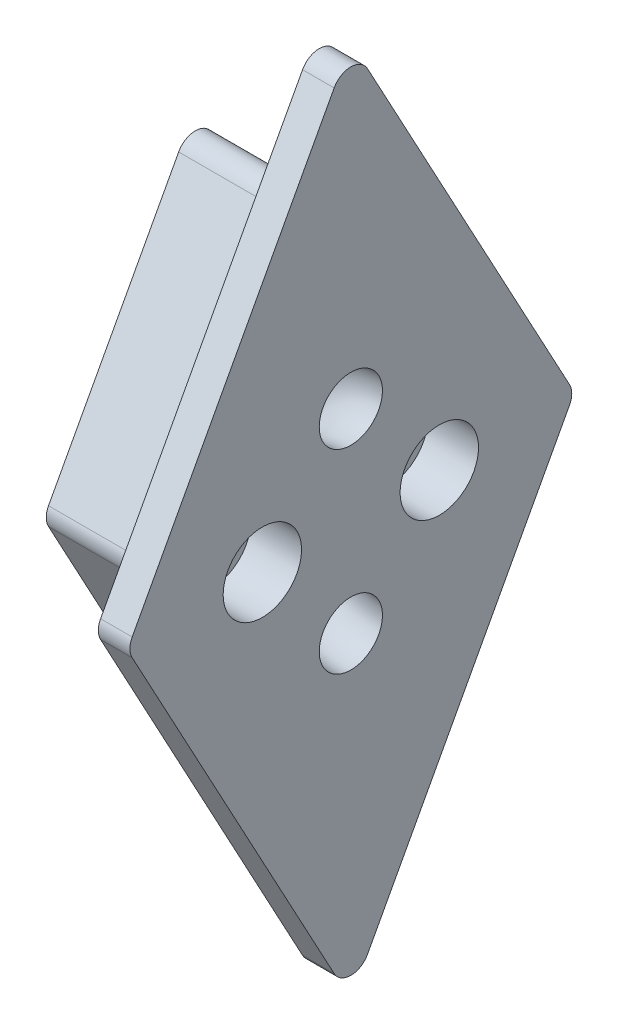
SolidWorks part; units mm, degrees
ref_plane "Front" through (0, 0, 0) normal (0, 0, 1) x (1, 0, 0)
ref_plane "Top" through (0, 0, 0) normal (0, 1, 0) x (1, 0, 0)
ref_plane "Right" through (0, 0, 0) normal (1, 0, 0) x (0, 0, -1)
sketch "Sketch1" plane through (0, 0, 0) normal (1, 0, 0) x (0, 0, -1)
  line L1 (0, -28.2575) -> (15.24, 0)
  line L2 (0, -28.2575) -> (-15.24, 0)
  line L3 (-15.24, 0) -> (0, 28.2575)
  line L4 (15.24, 0) -> (0, 28.2575)
  line L5 (0, -28.2575) -> (0, 28.2575) construction
  line L6 (-15.24, 0) -> (15.24, 0) construction
  point P0 (0, 0)
  dimension "D1" = 30.48
  dimension "D2" = 56.515
extrude "Boss-Extrude1" add sketch "Sketch1" along normal blind 12.446
sketch "Sketch6" plane through (12.446, 0, 0) normal (1, 0, 0) x (0, 0, -1)
  line L14 (-22.4547, 0) -> (0, -41.6347)
  line L15 (0, -41.6347) -> (22.4547, 0)
  line L16 (22.4547, 0) -> (0, 41.6347)
  line L17 (0, 41.6347) -> (-22.4547, 0)
  line L18 (-22.4547, 0) -> (0, -41.6347)
  line L19 (0, -41.6347) -> (22.4547, 0)
  line L20 (22.4547, 0) -> (0, 41.6347)
  line L21 (0, 41.6347) -> (-22.4547, 0)
  dimension "D1" = 6.35
extrude "Boss-Extrude3" add sketch "Sketch6" along normal blind 3.175
fillet "Fillet1" radius 1.905 8 edges at (14.0335, 41.6347, 0) (14.0335, 0, 22.4547) (14.0335, -41.6347, 0) (14.0335, 0, -22.4547) (6.223, -28.2575, 0) (6.223, 0, -15.24) (6.223, 0, 15.24) (6.223, 28.2575, 0)
sketch "Sketch7" plane through (0, 0, 0) normal (0, 1, 0) x (1, 0, 0)
  line L0 (0, 0) -> (25.2725, 0) construction
  line L1 (15.875, 0) -> (15.875, -10.3712) construction
  line L2 (15.621, 21.9669) -> (15.621, 1.6767) construction
  circle A0 centre (6.096, 0) radius 3.175
  dimension "D1" = 6.35
  dimension "D2" = 6.35
revolve "Cut-Revolve2" cut sketch "Sketch7" angle 360 about L1
sketch "Sketch8" plane through (15.621, 0, 0) normal (1, 0, 0) x (0, 0, -1)
  line L0 (0, 0) -> (8.89, 0) construction
  line L1 (0, 0) -> (0, 3.2594) construction
  circle A0 centre (8.89, 0) radius 3.937
  circle A1 centre (-8.89, 0) radius 3.937
  dimension "D2" = 7.874
  dimension "D1" = 8.89
extrude "Cut-Extrude3" cut sketch "Sketch8" against normal blind 5.08
sketch "Sketch9" plane through (10.541, 0, 0) normal (1, 0, 0) x (0, 0, -1)
  line L0 (0, 0) -> (0, 4.0921) construction
  circle A0 centre (8.89, 0) radius 2.5527
  circle A1 centre (-8.89, 0) radius 2.5527
  dimension "D1" = 5.1054
extrude "Cut-Extrude4" cut sketch "Sketch9" against normal through all
sketch "Sketch10" [suppressed] plane through (15.875, 0, 0) normal (1, 0, 0) x (0, 0, -1)
  line L0 (0, 0) -> (0, 8.2156) construction
  line L1 (13.6525, 2.7496) -> (8.89, 5.4993)
  line L2 (8.89, 5.4993) -> (4.1275, 2.7496)
  line L3 (4.1275, 2.7496) -> (4.1275, -2.7496)
  line L4 (4.1275, -2.7496) -> (8.89, -5.4993)
  line L5 (8.89, -5.4993) -> (13.6525, -2.7496)
  line L6 (13.6525, -2.7496) -> (13.6525, 2.7496)
  line L7 (-13.6525, -2.7496) -> (-13.6525, 2.7496)
  line L8 (-8.89, -5.4993) -> (-13.6525, -2.7496)
  line L9 (-4.1275, -2.7496) -> (-8.89, -5.4993)
  line L10 (-4.1275, 2.7496) -> (-4.1275, -2.7496)
  line L11 (-8.89, 5.4993) -> (-4.1275, 2.7496)
  line L12 (-13.6525, 2.7496) -> (-8.89, 5.4993)
  circle A0 centre (8.89, 0) radius 4.7625 construction
  circle A1 centre (-8.89, 0) radius 4.7625 construction
  point P1 (13.6525, 0)
  dimension "D1" = 9.525
sketch "Sketch11" [suppressed] plane through (15.621, 0, 0) normal (1, 0, 0) x (0, 0, -1)
  line L0 (0, 0) -> (8.89, 0) construction
  line L1 (0, 0) -> (0, 10.0261) construction
  circle A0 centre (8.89, 0) radius 3.175
  circle A1 centre (-8.89, 0) radius 3.175
  dimension "D2" = 6.35
  dimension "D1" = 8.89
extrude "Cut-Extrude6" [suppressed] cut sketch "Sketch11" against normal through all
